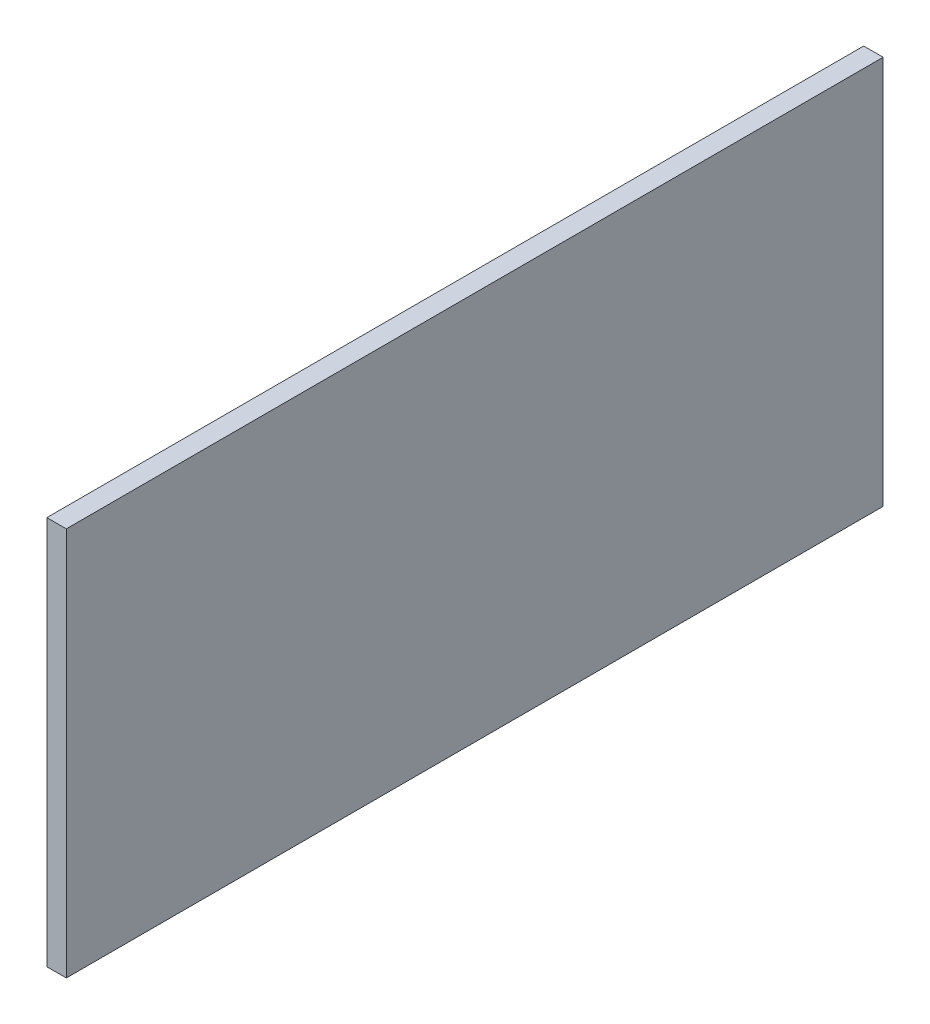
SolidWorks part; units mm, degrees
ref_plane "Plan de face" through (0, 0, 0) normal (0, 0, 1) x (1, 0, 0)
ref_plane "Plan de dessus" through (0, 0, 0) normal (0, 1, 0) x (1, 0, 0)
ref_plane "Plan de droite" through (0, 0, 0) normal (1, 0, 0) x (0, 0, -1)
sketch "Esquisse1" plane through (0, 0, 0) normal (1, 0, 0) x (0, 0, -1)
  line L0 (-52.3249, 47.3177) -> (-52.3249, 42.3177) construction
  line L1 (-52.3249, -52.6823) -> (157.6751, -52.6823)
  line L2 (-52.3249, -52.6823) -> (-52.3249, 47.3177)
  line L3 (-52.3249, 47.3177) -> (157.6751, 47.3177)
  line L4 (157.6751, -52.6823) -> (157.6751, 47.3177)
  line L5 (-52.3249, -52.6823) -> (157.6751, 47.3177) construction
  line L6 (-52.3249, 47.3177) -> (157.6751, -52.6823) construction
  line L7 (-52.3249, 47.3177) -> (157.6751, 47.3177) construction
  dimension "D1" = 100
extrude "Boss.-Extru.1" add sketch "Esquisse1" along normal blind 5
equation "\"h\"= 100"
equation "\"D1@Esquisse1\"=\"h\""
